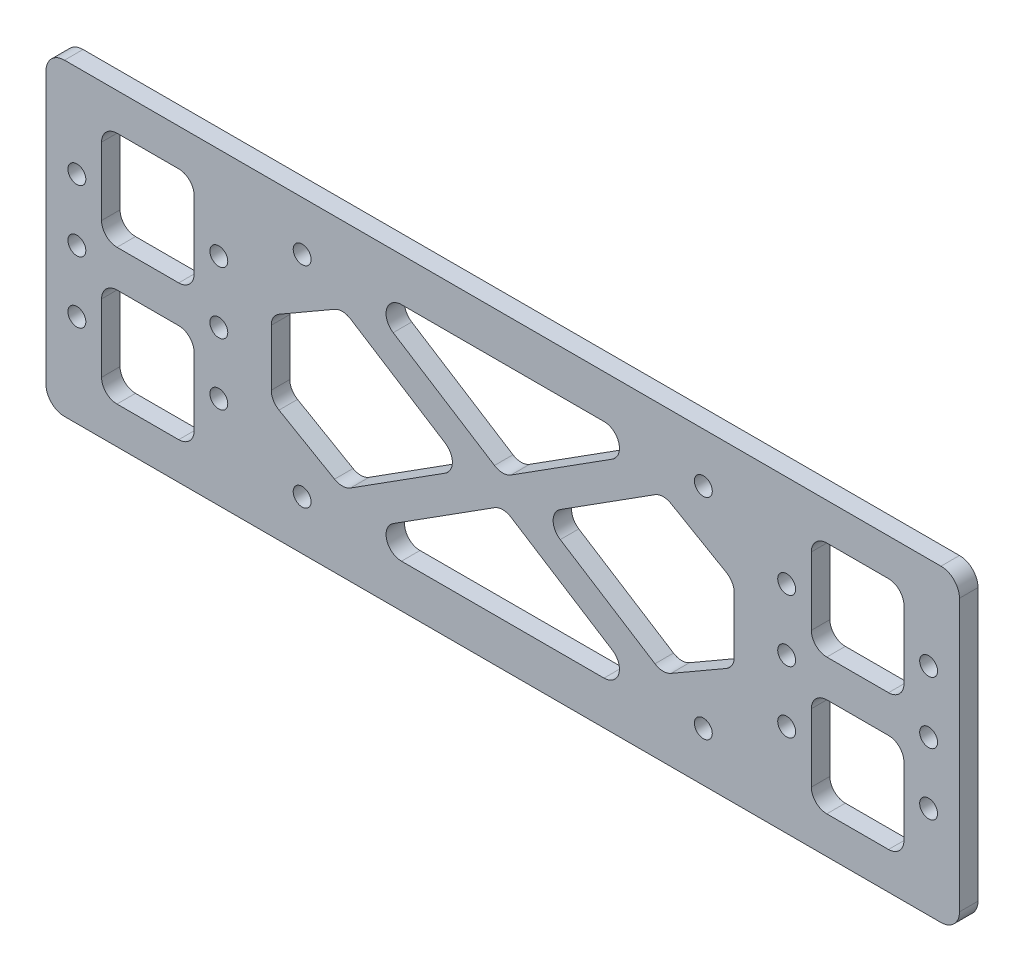
SolidWorks part; units mm, degrees
material "Thornel Mat VMA"
ref_plane "前视基准面" through (0, 0, 0) normal (0, 0, 1) x (1, 0, 0)
ref_plane "上视基准面" through (0, 0, 0) normal (0, 1, 0) x (1, 0, 0)
ref_plane "右视基准面" through (0, 0, 0) normal (1, 0, 0) x (0, 0, -1)
sketch "草图1" plane through (0, 0, 0) normal (0, 0, 1) x (1, 0, 0)
  line L1 (0, 0) -> (148, 0)
  line L2 (0, 0) -> (0, 50)
  line L3 (0, 50) -> (148, 50)
  line L4 (148, 0) -> (148, 50)
  dimension "D1" = 50
  dimension "D2" = 148
extrude "凸台-拉伸1" add sketch "草图1" along normal blind 3
sketch "草图2" plane through (0, 0, 3) normal (0, 0, 1) x (1, 0, 0)
  line L1 (5, 35) -> (28, 35) construction
  line L2 (5, 35) -> (5, 15) construction
  line L3 (5, 15) -> (28, 15) construction
  line L4 (28, 35) -> (28, 15) construction
  line L6 (120, 35) -> (143, 35) construction
  line L7 (120, 35) -> (120, 15) construction
  line L8 (120, 15) -> (143, 15) construction
  line L9 (143, 35) -> (143, 15) construction
  line L10 (5, 25) -> (28, 25) construction
  line L12 (120, 25) -> (143, 25) construction
  line L14 (16.5, 15) -> (131.5, 15) construction
  line L17 (41.5, 42) -> (106.5, 42) construction
  line L18 (41.5, 42) -> (41.5, 8) construction
  line L19 (41.5, 8) -> (106.5, 8) construction
  line L20 (106.5, 42) -> (106.5, 8) construction
  line L23 (106.5, 25) -> (143, 25) construction
  line L24 (143, 25) -> (148, 25) construction
  line L25 (148, 0) -> (148, 50) construction
  line L27 (74, 42) -> (74, 50) construction
  line L28 (148, 50) -> (0, 50) construction
  circle A0 centre (5, 35) radius 1.45
  circle A1 centre (5, 25) radius 1.45
  circle A2 centre (5, 15) radius 1.45
  circle A3 centre (28, 15) radius 1.45
  circle A4 centre (28, 25) radius 1.45
  circle A5 centre (28, 35) radius 1.45
  circle A6 centre (120, 35) radius 1.45
  circle A7 centre (120, 25) radius 1.45
  circle A8 centre (120, 15) radius 1.45
  circle A9 centre (143, 15) radius 1.45
  circle A10 centre (143, 25) radius 1.45
  circle A11 centre (143, 35) radius 1.45
  circle A12 centre (41.5, 42) radius 1.45
  circle A13 centre (106.5, 42) radius 1.45
  circle A14 centre (106.5, 8) radius 1.45
  circle A15 centre (41.5, 8) radius 1.45
  point P42 (131.5, 15)
  dimension "D3" = 20
  dimension "D4" = 23
  dimension "D5" = 2.9
  dimension "D6" = 2.9
  dimension "D1" = 23
  dimension "D9" = 2.9
  dimension "D10" = 2.9
  dimension "D11" = 2.9
  dimension "D14" = 2.9
  dimension "D15" = 2.9
  dimension "D16" = 2.9
  dimension "D17" = 115
  dimension "D20" = 2.9
  dimension "D21" = 2.9
  dimension "D22" = 2.9
  dimension "D23" = 34
  dimension "D7" = 2.9
  dimension "D8" = 2.9
  dimension "D12" = 2.9
  dimension "D13" = 2.9
  dimension "D19" = 2.9
  dimension "D2" = 20
  dimension "D18" = 65
  dimension "D24" = 13.5
extrude "切除-拉伸1" cut sketch "草图2" against normal through all
sketch "草图3" plane through (0, 0, 3) normal (0, 0, 1) x (1, 0, 0)
  line L0 (49, 43) -> (99, 43)
  line L1 (99, 43) -> (74, 27.111)
  line L2 (74, 27.111) -> (49, 43)
  line L4 (48.0591, 12.3264) -> (68, 25)
  line L5 (68, 25) -> (48.0591, 37.6736)
  line L7 (99.9409, 12.3264) -> (80, 25)
  line L8 (80, 25) -> (99.9409, 37.6736)
  line L9 (74, 22.889) -> (49, 7)
  line L10 (49, 7) -> (99, 7)
  line L11 (99, 7) -> (74, 22.889)
  line L12 (148, 50) -> (0, 50) construction
  line L13 (0, 0) -> (148, 0) construction
  line L14 (48.0591, 37.6736) -> (36.5, 31)
  line L15 (9, 44) -> (24, 44)
  line L16 (9, 44) -> (9, 28)
  line L17 (9, 28) -> (24, 28)
  line L18 (24, 44) -> (24, 28)
  line L19 (9, 22) -> (24, 22)
  line L20 (9, 22) -> (9, 6)
  line L21 (9, 6) -> (24, 6)
  line L22 (24, 22) -> (24, 6)
  line L31 (124, 44) -> (139, 44)
  line L32 (124, 44) -> (124, 28)
  line L33 (124, 28) -> (139, 28)
  line L34 (139, 44) -> (139, 28)
  line L35 (124, 22) -> (139, 22)
  line L36 (124, 22) -> (124, 6)
  line L37 (124, 6) -> (139, 6)
  line L38 (139, 22) -> (139, 6)
  line L39 (36.5, 31) -> (36.5, 19)
  line L40 (36.5, 19) -> (48.0591, 12.3264)
  line L41 (99.9409, 37.6736) -> (111.5, 31)
  line L42 (111.5, 31) -> (111.5, 19)
  line L43 (111.5, 19) -> (99.9409, 12.3264)
  line L44 (74, 50) -> (74, 0) construction
  circle A2 centre (5, 35) radius 1.45 construction
  circle A3 centre (5, 15) radius 1.45 construction
  circle A4 centre (28, 35) radius 1.45 construction
  circle A5 centre (28, 15) radius 1.45 construction
  circle A6 centre (5, 25) radius 1.45 construction
  circle A7 centre (120, 35) radius 1.45 construction
  circle A8 centre (143, 35) radius 1.45 construction
  circle A9 centre (120, 25) radius 1.45 construction
  circle A10 centre (120, 15) radius 1.45 construction
  circle A11 centre (143, 15) radius 1.45 construction
  point P56 (74, 43)
  point P59 (74, 7)
  dimension "D7" = 50
  dimension "D10" = 4
  dimension "D14" = 3
  dimension "D1" = 7
  dimension "D2" = 7
  dimension "D3" = 5
  dimension "D4" = 5
  dimension "D5" = 5
  dimension "D6" = 5
  dimension "D8" = 37.5
  dimension "D9" = 4
  dimension "D11" = 4
  dimension "D12" = 4
  dimension "D13" = 3
  dimension "D15" = 6
  dimension "D16" = 6
  dimension "D17" = 4
  dimension "D18" = 4
  dimension "D19" = 6
  dimension "D20" = 6
  dimension "D21" = 3
  dimension "D22" = 4
  dimension "D23" = 3
  dimension "D24" = 4
  dimension "D25" = 37.5
  dimension "D26" = 12
  dimension "D27" = 120
  dimension "D28" = 120
  dimension "D29" = 12
extrude "切除-拉伸2" cut sketch "草图3" against normal blind 10
fillet "圆角1" radius 3 4 edges at (148, 0, 1.5) (148, 50, 1.5) (0, 50, 1.5) (0, 0, 1.5)
fillet "圆角2" radius 2.5 32 edges at (49, 43, 1.5) (99, 43, 1.5) (74, 27.111, 1.5) (124, 22, 1.5) (139, 22, 1.5) (139, 6, 1.5) (124, 6, 1.5) (9, 44, 1.5) (24, 44, 1.5) (9, 28, 1.5) (124, 44, 1.5) (139, 44, 1.5) (139, 28, 1.5) (124, 28, 1.5) (48.0591, 37.6736, 1.5) (68, 25, 1.5) (48.0591, 12.3264, 1.5) (36.5, 19, 1.5) (36.5, 31, 1.5) (111.5, 31, 1.5) (111.5, 19, 1.5) (99.9409, 12.3264, 1.5) (80, 25, 1.5) (99.9409, 37.6736, 1.5) (99, 7, 1.5) (49, 7, 1.5) (74, 22.889, 1.5) (9, 22, 1.5) (24, 22, 1.5) (24, 6, 1.5) (9, 6, 1.5) (24, 28, 1.5)
